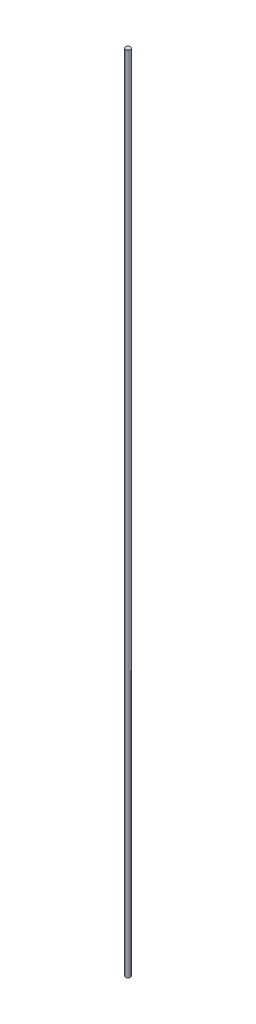
SolidWorks part; units mm, degrees
ref_plane "Front Plane" through (0, 0, 0) normal (0, 0, 1) x (1, 0, 0)
ref_plane "Top Plane" through (0, 0, 0) normal (0, 1, 0) x (1, 0, 0)
ref_plane "Right Plane" through (0, 0, 0) normal (1, 0, 0) x (0, 0, -1)
sketch "Sketch1" plane through (0, 0, 0) normal (0, 1, 0) x (1, 0, 0)
  circle A0 centre (0, 0) radius 12.5
  dimension "D1" = 25
extrude "Boss-Extrude1" add sketch "Sketch1" along normal blind 4033
